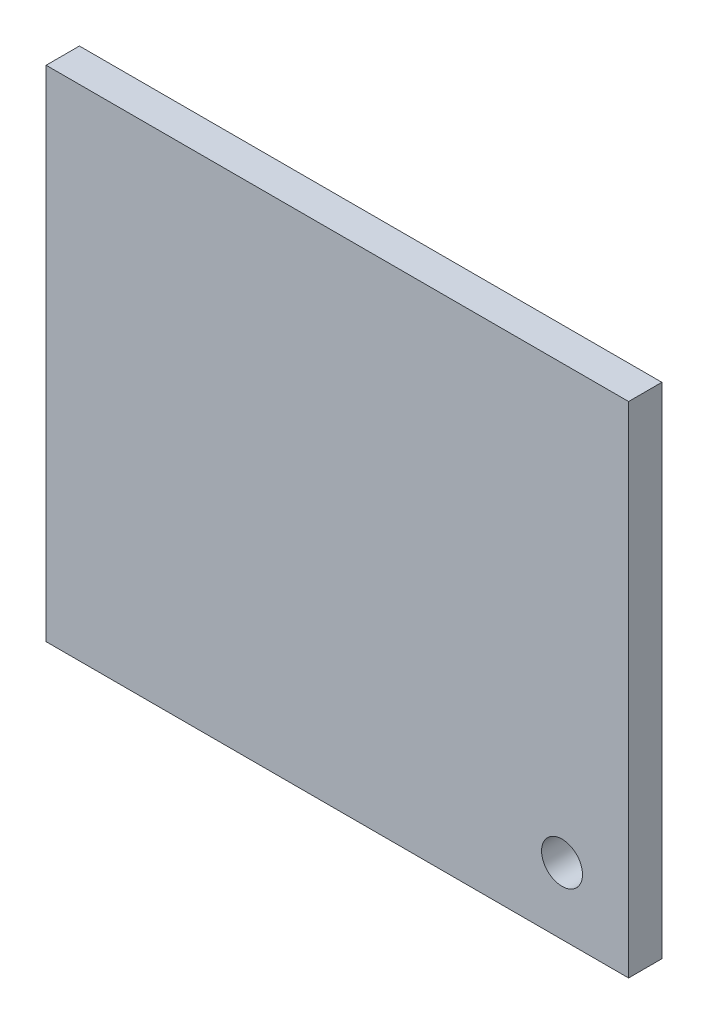
SolidWorks part; units mm, degrees
ref_plane "Front Plane" through (0, 0, 0) normal (0, 0, 1) x (1, 0, 0)
ref_plane "Top Plane" through (0, 0, 0) normal (0, 1, 0) x (1, 0, 0)
ref_plane "Right Plane" through (0, 0, 0) normal (1, 0, 0) x (0, 0, -1)
sketch "Sketch1" plane through (0, 0, 0) normal (0, 0, 1) x (1, 0, 0)
  line L1 (-17.5, -15) -> (17.5, -15)
  line L2 (-17.5, -15) -> (-17.5, 15)
  line L3 (-17.5, 15) -> (17.5, 15)
  line L4 (17.5, -15) -> (17.5, 15)
  line L5 (-17.5, -15) -> (17.5, 15) construction
  line L6 (-17.5, 15) -> (17.5, -15) construction
  point P0 (0, 0)
  dimension "D1" = 35
  dimension "D2" = 30
extrude "Boss-Extrude1" add sketch "Sketch1" along normal blind 2
sketch "Sketch2" plane through (0, 0, 2) normal (0, 0, 1) x (1, 0, 0)
  line L0 (17.5, -15) -> (17.5, 15) construction
  line L1 (-17.5, -15) -> (17.5, -15) construction
  circle A0 centre (13.5, -11) radius 1.23
  dimension "D1" = 2.46
  dimension "D2" = 4
  dimension "D3" = 4
extrude "Cut-Extrude1" cut sketch "Sketch2" against normal blind 2
